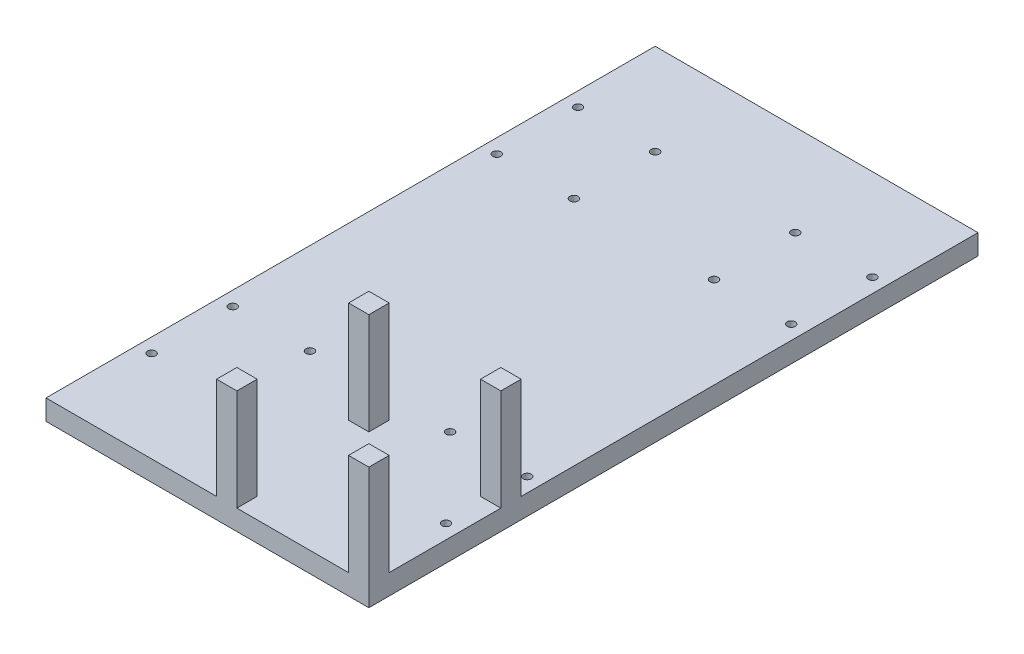
SolidWorks part; units mm, degrees
material "Pine"
ref_plane "Front Plane" through (0, 0, 0) normal (0, 0, 1) x (1, 0, 0)
ref_plane "Top Plane" through (0, 0, 0) normal (0, 1, 0) x (1, 0, 0)
ref_plane "Right Plane" through (0, 0, 0) normal (1, 0, 0) x (0, 0, -1)
sketch "Sketch3" plane through (0, 0, 0) normal (0, 1, 0) x (1, 0, 0)
  line L1 (-79.5, -150) -> (79.5, -150)
  line L2 (-79.5, -150) -> (-79.5, 150)
  line L3 (-79.5, 150) -> (79.5, 150)
  line L4 (79.5, -150) -> (79.5, 150)
  line L5 (-79.5, -150) -> (79.5, 150) construction
  line L6 (-79.5, 150) -> (79.5, -150) construction
  point P0 (0, 0)
  dimension "D1" = 159
  dimension "D2" = 300
extrude "Boss-Extrude1" add sketch "Sketch3" along normal blind 10
sketch "Sketch4" plane through (0, 10, 0) normal (0, 1, 0) x (1, 0, 0)
  line L0 (79.5, -150) -> (79.5, 150) construction
  line L1 (79.5, -150) -> (69.5, -150)
  line L2 (79.5, -150) -> (79.5, -140)
  line L3 (79.5, -75) -> (69.5, -75)
  line L4 (4.5, -150) -> (4.5, -140)
  line L5 (-79.5, -150) -> (79.5, -150) construction
  line L6 (14.5, -150) -> (14.5, -140)
  line L7 (69.5, -75) -> (69.5, -85)
  line L8 (14.5, -75) -> (4.5, -75)
  line L9 (14.5, -150) -> (4.5, -150)
  line L10 (4.5, -140) -> (14.5, -140)
  line L11 (4.5, -85) -> (14.5, -85)
  line L12 (69.5, -85) -> (79.5, -85)
  line L13 (69.5, -140) -> (79.5, -140)
  line L14 (4.5, -85) -> (4.5, -75)
  line L15 (14.5, -85) -> (14.5, -75)
  line L16 (69.5, -140) -> (69.5, -150)
  line L17 (79.5, -85) -> (79.5, -75)
  point P20 (74.5, -140)
  dimension "D1" = 0
  dimension "D2" = 0
  dimension "D3" = 75
  dimension "D4" = 75
  dimension "D5" = 10
  dimension "D6" = 10
  dimension "D7" = 10
  dimension "D8" = 10
  dimension "D9" = 10
extrude "Boss-Extrude2" add sketch "Sketch4" along normal blind 50
sketch "Sketch7" plane through (0, 0, 0) normal (0, -1, 0) x (1, 0, 0)
  line L0 (79.5, 150) -> (79.5, -150) construction
  line L1 (-79.5, 150) -> (79.5, 150) construction
  line L2 (-72.5, -105) -> (72.5, -105) construction
  line L3 (-72.5, -65) -> (72.5, -65) construction
  line L4 (-72.5, 65) -> (72.5, 65) construction
  line L5 (-72.5, 105) -> (72.5, 105) construction
  line L6 (-79.5, -150) -> (-79.5, 150) construction
  circle A0 centre (34.5, -105) radius 2
  circle A1 centre (72.5, -105) radius 2
  circle A2 centre (72.5, -65) radius 2
  circle A3 centre (34.5, -65) radius 2
  circle A4 centre (-34.5, -65) radius 2
  circle A5 centre (-72.5, -65) radius 2
  circle A6 centre (-34.5, -105) radius 2
  circle A7 centre (-72.5, -105) radius 2
  circle A8 centre (-72.5, 65) radius 2
  circle A9 centre (-72.5, 105) radius 2
  circle A10 centre (-34.5, 105) radius 2
  circle A11 centre (-34.5, 65) radius 2
  circle A12 centre (34.5, 105) radius 2
  circle A13 centre (72.5, 105) radius 2
  circle A14 centre (72.5, 65) radius 2
  circle A15 centre (34.5, 65) radius 2
  point P36 (0, 0)
  point P39 (0, 0)
  point P40 (0, 0)
  point P41 (0, 0)
  point P42 (0, 0)
  dimension "D17" = 40
  dimension "D12" = 7
  dimension "D25" = 7
  dimension "D4" = 7
  dimension "D1" = 38
  dimension "D2" = 40
  dimension "D3" = 38
  dimension "D5" = 38
  dimension "D6" = 40
  dimension "D7" = 38
  dimension "D8" = 130
  dimension "D9" = 38
  dimension "D10" = 40
  dimension "D11" = 38
  dimension "D13" = 38
  dimension "D14" = 40
  dimension "D15" = 38
  dimension "D16" = 7
  dimension "D18" = 55.1725
  dimension "D19" = 40
  dimension "D20" = 55.1725
  dimension "D21" = 40
  dimension "D22" = 40
  dimension "D23" = 55.1725
  dimension "D24" = 55.1725
  dimension "D27" = 45
extrude "Cut-Extrude2" cut sketch "Sketch7" against normal blind 10
sketch "Sketch8" plane through (0, 10, 0) normal (0, 1, 0) x (1, 0, 0)
  line L0 (-79.5, -150) -> (4.5, -150) construction
  line L1 (-79.5, 150) -> (-79.5, -150) construction
  line L2 (79.5, -75) -> (79.5, 150) construction
  circle A0 centre (-14.5, -45) radius 4
  circle A1 centre (5.5, -45) radius 4
  circle A5 centre (-14.5, 30) radius 4
  circle A6 centre (5.5, 30) radius 4
  circle A7 centre (24.5, -7.5) radius 4
  circle A8 centre (44.5, -7.5) radius 4
  dimension "D1" = 8
  dimension "D2" = 8
  dimension "D4" = 8
  dimension "D5" = 8
  dimension "D7" = 8
  dimension "D8" = 8
  dimension "D3" = 20
  dimension "D6" = 20
  dimension "D9" = 20
  dimension "D10" = 105
  dimension "D11" = 65
  dimension "D12" = 65
  dimension "D13" = 75
  dimension "D14" = 37.5
  dimension "D15" = 35
extrude "Cut-Extrude3" [suppressed] cut sketch "Sketch8" against normal blind 10
